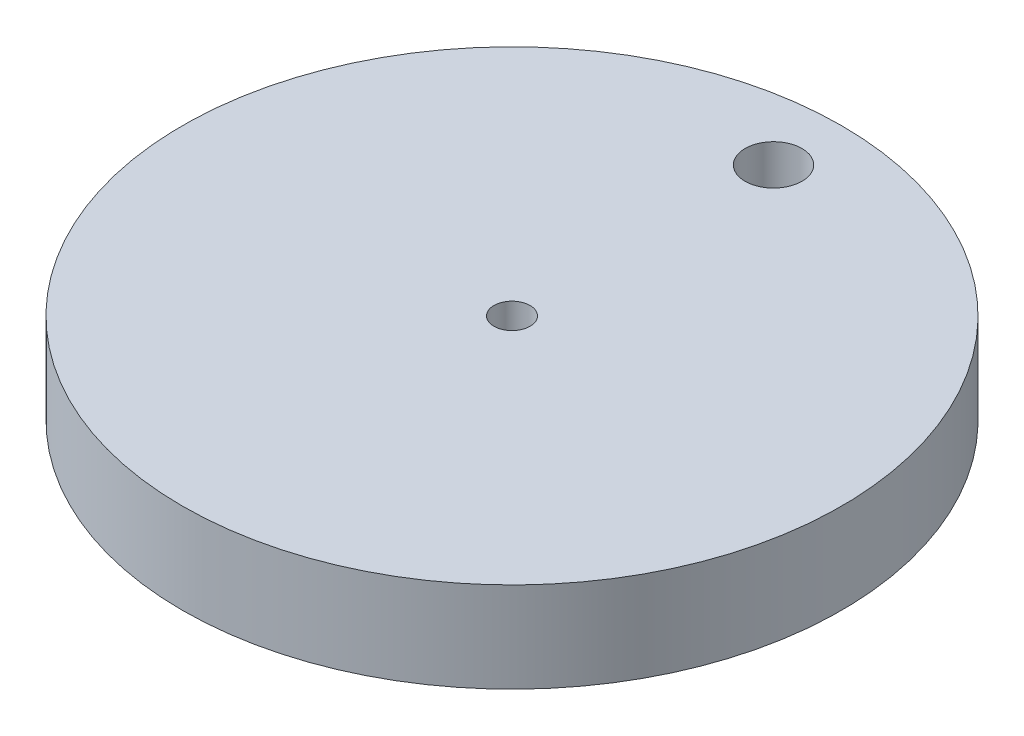
SolidWorks part; units mm, degrees
ref_plane "Front Plane" through (0, 0, 0) normal (0, 0, 1) x (1, 0, 0)
ref_plane "Top Plane" through (0, 0, 0) normal (0, 1, 0) x (1, 0, 0)
ref_plane "Right Plane" through (0, 0, 0) normal (1, 0, 0) x (0, 0, -1)
sketch "Sketch1" plane through (0, 0, 0) normal (0, 1, 0) x (1, 0, 0)
  line L0 (0, 0) -> (0, 46.355) construction
  circle A0 centre (0, 0) radius 46.355
  circle A1 centre (0, 0) radius 2.54
  circle A2 centre (0, 36.785) radius 4
  dimension "D1" = 92.71
  dimension "D2" = 5.08
  dimension "D3" = 8
extrude "Boss-Extrude1" add sketch "Sketch1" along normal blind 12.7
